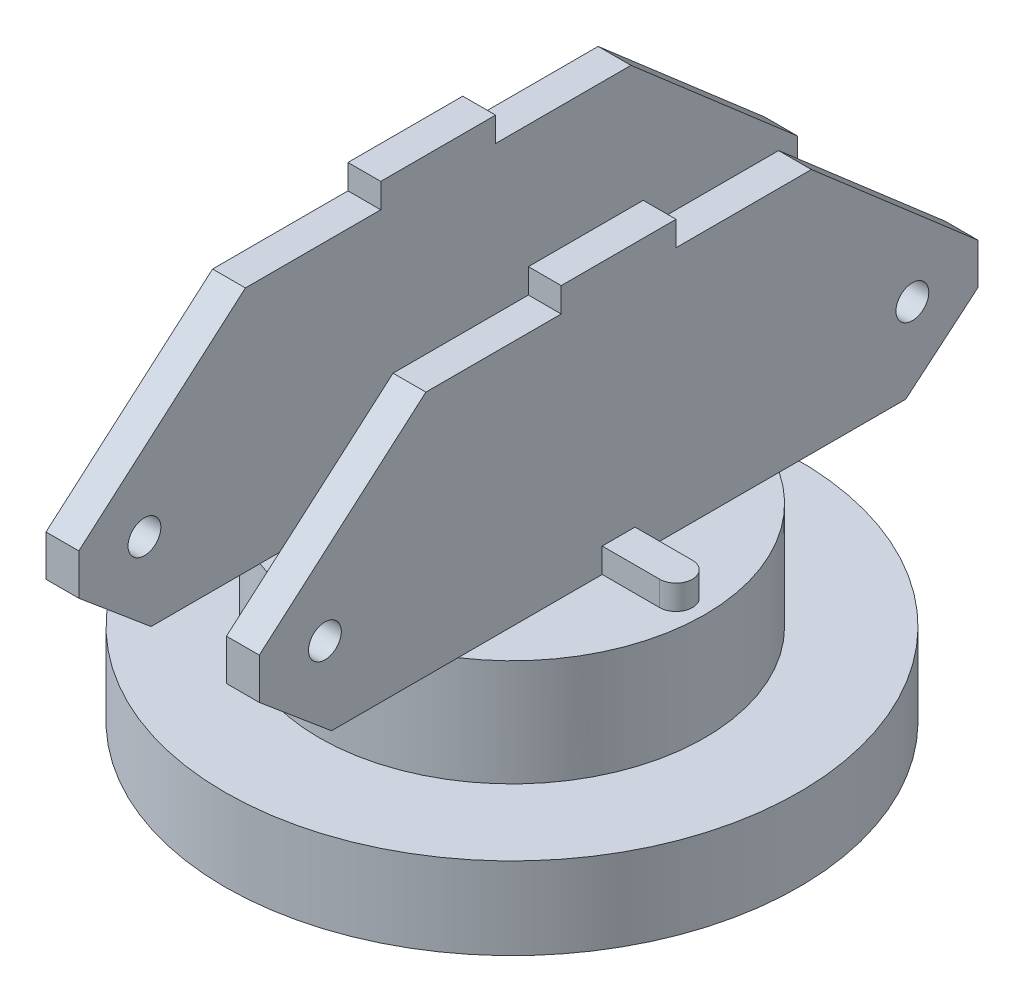
SolidWorks part; units mm, degrees
ref_plane "Front Plane" through (0, 0, 0) normal (0, 0, 1) x (1, 0, 0)
ref_plane "Top Plane" through (0, 0, 0) normal (0, 1, 0) x (1, 0, 0)
ref_plane "Right Plane" through (0, 0, 0) normal (1, 0, 0) x (0, 0, -1)
sketch "Sketch1" plane through (0, 0, 0) normal (0, 1, 0) x (1, 0, 0)
  circle A0 centre (0, 0) radius 17.5
  dimension "D1" = 35
extrude "Boss-Extrude1" add sketch "Sketch1" along normal blind 5
sketch "Sketch2" plane through (0, 5, 0) normal (0, 1, 0) x (1, 0, 0)
  circle A0 centre (0, 0) radius 11.75
  dimension "D1" = 23.5
extrude "Boss-Extrude2" add sketch "Sketch2" along normal blind 6.5
sketch "Sketch3" plane through (0, 11.5, 0) normal (0, 1, 0) x (1, 0, 0)
  line L0 (0, 0) -> (-6.5, 0) construction
  line L1 (-6.5, 0) -> (-6.5, 1)
  line L2 (-6.5, 1) -> (-10, 1)
  line L4 (-10, -1) -> (-6.5, -1)
  line L5 (-6.5, -1) -> (-6.5, 0)
  line L6 (0, 11.75) -> (0, -11.75) construction
  line L7 (6.5, -1) -> (6.5, 0)
  line L8 (10, -1) -> (6.5, -1)
  line L9 (6.5, 1) -> (10, 1)
  line L10 (6.5, 0) -> (6.5, 1)
  arc A0 (-10, 1) -> (-10, -1) centre (-10, 0) ccw
  circle A1 centre (0, 0) radius 11.75 construction
  circle A2 centre (0, 0) radius 11.75 construction
  arc A3 (10, 1) -> (10, -1) centre (10, 0) cw
  dimension "D1" = 2
  dimension "D2" = 1
  dimension "D3" = 3.5
extrude "Boss-Extrude4" add sketch "Sketch3" along normal blind 1.5
sketch "Sketch4" plane through (-6.5, 0, 0) normal (1, 0, 0) x (0, 0, -1)
  line L0 (-17.5, 11.5) -> (17.5, 11.5)
  line L2 (17.5, 11.5) -> (21.9048, 15.196)
  line L3 (21.9048, 15.196) -> (21.9048, 17.696)
  line L6 (11.75, 26.5) -> (21.9048, 17.696)
  line L7 (-3.5, 28) -> (3.5, 28)
  line L8 (3.5, 28) -> (3.5, 26.5)
  line L9 (3.5, 26.5) -> (11.75, 26.5)
  line L10 (-3.5, 26.5) -> (-11.75, 26.5)
  line L11 (-3.5, 28) -> (-3.5, 26.5)
  line L12 (-11.75, 26.5) -> (-21.9048, 17.696)
  line L13 (-21.9048, 15.196) -> (-21.9048, 17.696)
  line L14 (-17.5, 11.5) -> (-21.9048, 15.196)
  circle A0 centre (17.9048, 16.446) radius 1
  circle A1 centre (-17.9048, 16.446) radius 1
  dimension "D5" = 2
  dimension "D1" = 140
  dimension "D2" = 2.5
ref_plane "Plane1" through (0, 0, 0) normal (1, 0, 0) x (0, 0, -1)
extrude "Boss-Extrude5" add sketch "Sketch4" along normal blind 2
mirror "Mirror1" about plane through (0, 0, 0) normal (1, 0, 0) of "Boss-Extrude5"
sketch "Sketch5" plane through (0, 0, 0) normal (0, -1, 0) x (1, 0, 0)
  circle A0 centre (0, 0) radius 5
  dimension "D1" = 10
extrude "Cut-Extrude1" cut sketch "Sketch5" against normal blind 5
